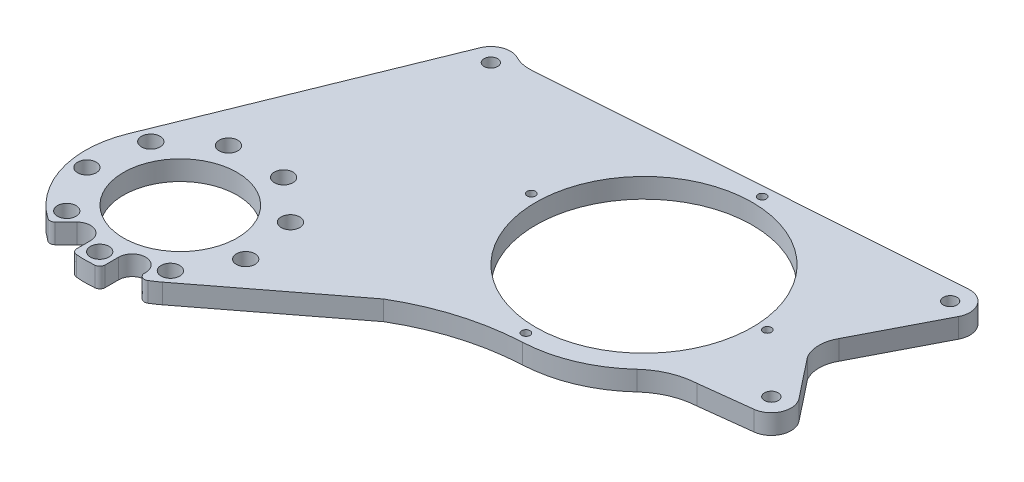
SolidWorks part; units mm, degrees
material "6061-T6 (SS)"
ref_plane "X-Y Datum" through (0, 0, 0) normal (0, 0, 1) x (1, 0, 0)
ref_plane "X-Z Datum" through (0, 0, 0) normal (0, 1, 0) x (1, 0, 0)
ref_plane "Y-Z Datum" through (0, 0, 0) normal (1, 0, 0) x (0, 0, -1)
sketch "Sketch1" plane through (0, 0, 0) normal (0, 1, 0) x (-1, 0, 0)
  line L0 (-685.8, 104.2174) -> (-575.31, 72.8215) construction
  line L1 (-575.31, 72.8215) -> (-438.15, 160.02) construction
  line L2 (-685.8, 0) -> (-575.31, 72.8215) construction
  line L3 (-568.96, 0) -> (-457.2, 0) construction
  line L4 (-575.31, 72.8215) -> (-457.2, 0) construction
  line L5 (-663.9188, 4.4766) -> (-466.5721, 18.457)
  line L6 (-673.0578, 18.3429) -> (-653.3465, 56.5717)
  line L8 (-414.9501, 197.3367) -> (-420.215, 192.0718)
  line L9 (-431.3112, 196.668) -> (-431.3112, 203.2407)
  line L10 (-444.9888, 203.2407) -> (-444.9888, 196.668)
  line L11 (-457.9888, 196.668) -> (-457.9888, 197.245)
  line L12 (-685.8, 0) -> (-568.96, 0) construction
  line L13 (-685.8, 104.2174) -> (-685.8, 0) construction
  line L16 (-444.6912, 21.5522) -> (-395.5458, 142.7431)
  line L17 (-668.8428, 91.3721) -> (-653.3465, 71.7463)
  line L18 (-526.6297, 150.1211) -> (-466.1201, 196.5067)
  line L19 (-662.4857, 106.7339) -> (-637.7531, 109.6583)
  circle A0 centre (-685.8, 104.2174) radius 12.7 construction
  circle A1 centre (-685.8, 0) radius 12.7 construction
  circle A2 centre (-457.2, 0) radius 12.7 construction
  circle A3 centre (-438.15, 199.02) radius 4.5 construction
  circle A4 centre (-438.15, 160.02) radius 39 construction
  circle A5 centre (-661.3672, 97.2748) radius 9.525 construction
  circle A6 centre (-664.5919, 13.9778) radius 9.525 construction
  circle A7 centre (-453.518, 25.1317) radius 9.525 construction
  circle A8 centre (-438.15, 160.02) radius 27.4955
  arc A10 (-466.5721, 18.457) -> (-457.9605, 16.7062) centre (-465.2583, 2.8655) cw
  arc A11 (-411.6923, 197.6179) -> (-395.5458, 142.7431) centre (-438.15, 160.02) cw
  arc A13 (-673.0578, 18.3429) -> (-663.9188, 4.4766) centre (-664.5919, 13.9778) ccw
  arc A14 (-457.9605, 16.7062) -> (-444.6912, 21.5522) centre (-453.518, 25.1317) ccw
  arc A16 (-461.8375, 199.4219) -> (-411.6923, 197.6179) centre (-438.15, 160.02) ccw construction
  arc A17 (-411.6923, 197.6179) -> (-414.9501, 197.3367) centre (-413.1541, 195.5407) ccw
  arc A18 (-431.3112, 196.668) -> (-420.215, 192.0718) centre (-424.8112, 196.668) ccw
  arc A19 (-431.3112, 203.2407) -> (-433.5998, 205.7683) centre (-433.8512, 203.2407) ccw
  arc A20 (-433.5998, 205.7683) -> (-442.7002, 205.7683) centre (-438.15, 160.02) ccw
  arc A21 (-442.7002, 205.7683) -> (-444.9888, 203.2407) centre (-442.4488, 203.2407) ccw
  arc A22 (-457.9888, 196.668) -> (-444.9888, 196.668) centre (-451.4888, 196.668) ccw
  arc A23 (-457.9888, 197.245) -> (-461.8375, 199.4219) centre (-460.5288, 197.245) ccw
  arc A24 (-653.3465, 71.7463) -> (-653.3465, 56.5717) centre (-666.7462, 64.159) cw
  arc A25 (-466.1201, 196.5067) -> (-461.8375, 199.4219) centre (-438.15, 160.02) cw
  arc A26 (-637.7531, 109.6583) -> (-617.3, 118.3187) centre (-639.5837, 142.4636) ccw
  arc A27 (-526.6297, 150.1211) -> (-578.3125, 134.6611) centre (-583.7676, 247.0155) cw
  circle A31 centre (-632.4025, 70.2575) radius 2
  arc A32 (-518.2175, 72.2575) -> (-518.2175, 68.2575) centre (-518.2175, 70.2575) ccw
  arc A33 (-518.2175, 68.2575) -> (-518.2175, 72.2575) centre (-518.2175, 70.2575) ccw
  arc A34 (-575.31, 17.6715) -> (-575.31, 13.6715) centre (-575.31, 15.6715) ccw
  arc A35 (-575.31, 13.6715) -> (-575.31, 17.6715) centre (-575.31, 15.6715) ccw
  arc A36 (-575.31, 131.9715) -> (-575.31, 127.9715) centre (-575.31, 129.9715) ccw
  arc A37 (-575.31, 127.9715) -> (-575.31, 131.9715) centre (-575.31, 129.9715) ccw
  circle A38 centre (-575.31, 72.8215) radius 61.9125 construction
  circle A39 centre (-575.31, 72.8215) radius 52.3875
  arc A40 (-617.3, 118.3187) -> (-578.3125, 134.6611) centre (-575.31, 72.8215) cw
  arc A41 (-668.8428, 91.3721) -> (-662.4857, 106.7339) centre (-661.3672, 97.2748) cw
  circle A42 centre (-661.3672, 97.2748) radius 3.3
  circle A43 centre (-664.5919, 13.9778) radius 3.3
  circle A44 centre (-453.518, 25.1317) radius 3.3
  dimension "D5" = 25.4
  dimension "D6" = 685.8
  dimension "D7" = 123.825
  dimension "D8" = 104.775
  dimension "D9" = 4
  dimension "D13" = 45.974
  dimension "D14" = 19.05
  dimension "D15" = 25.4
  dimension "D16" = 114.864
  dimension "D19" = 25.4
  dimension "D20" = 9
  dimension "D21" = 3.682
  dimension "D32" = 57.15
  dimension "D18" = 6.5
  dimension "D23" = 78
  dimension "D24" = 15.3987
  dimension "D35" = 32.8564
  dimension "D22" = 54.991
  dimension "D26" = 15.6468
  dimension "D38" = 112.4868
  dimension "D41" = 6.6
  dimension "D1" = 104.2174
  dimension "D2" = 228.6
  dimension "D3" = 247.65
  dimension "D4" = 160.02
  dimension "D10" = 575.31
  dimension "D11" = 72.8215
  dimension "D12" = 116.84
  dimension "D17" = 25.4
  dimension "D25" = 22.3788
  dimension "D27" = 57.0925
  dimension "D28" = 2.564
  dimension "D29" = 2.564
  dimension "D30" = 57.0925
  dimension "D31" = 57.15
  dimension "D33" = 18.457
  dimension "D34" = 1.4888
  dimension "D36" = 12.3835
  dimension "D37" = 23.6141
  dimension "D39" = 9.8989
  dimension "D40" = 88.4797
extrude "Boss-Extrude1" add sketch "Sketch1" along normal blind 9.525
hole_wizard "M8 Clearance Hole1" positions "Sketch5" profile "Sketch4" hole size "M8" standard "ANSI Metric" end condition through all
sketch "Sketch5" plane through (0, 0, 0) normal (0, -1, 0) x (-1, 0, 0)
  point P0 (-438.15, -199.02)
sketch "Sketch4" plane through (438.15, 0, 199.02) normal (1, 0, 0) x (0, 0, -1)
  line L0 (0, 0) -> (0, 9.525)
  line L1 (0, 9.525) -> (4.5, 9.525)
  line L2 (4.5, 9.525) -> (4.5, 0.025)
  line L3 (4.5, 0.025) -> (4.525, 0)
  line L5 (4.525, 0) -> (0, 0)
  line L6 (-4.5, 0.025) -> (-4.525, 0) construction
  line L11 (0, -6.35) -> (0, 107.95) construction
  dimension "Thru Hole Dia." = 9
  dimension "Thru Hole Depth" = 9.525
  dimension "Near C'Sink Dia." = 9.05
  dimension "Near C'Sink Angle" = 90
pattern_circular "CirPattern1" count 9 over 360 about axis through (438.15, 0, 160.02) along (0, 1, 0) of "M8 Clearance Hole1"
